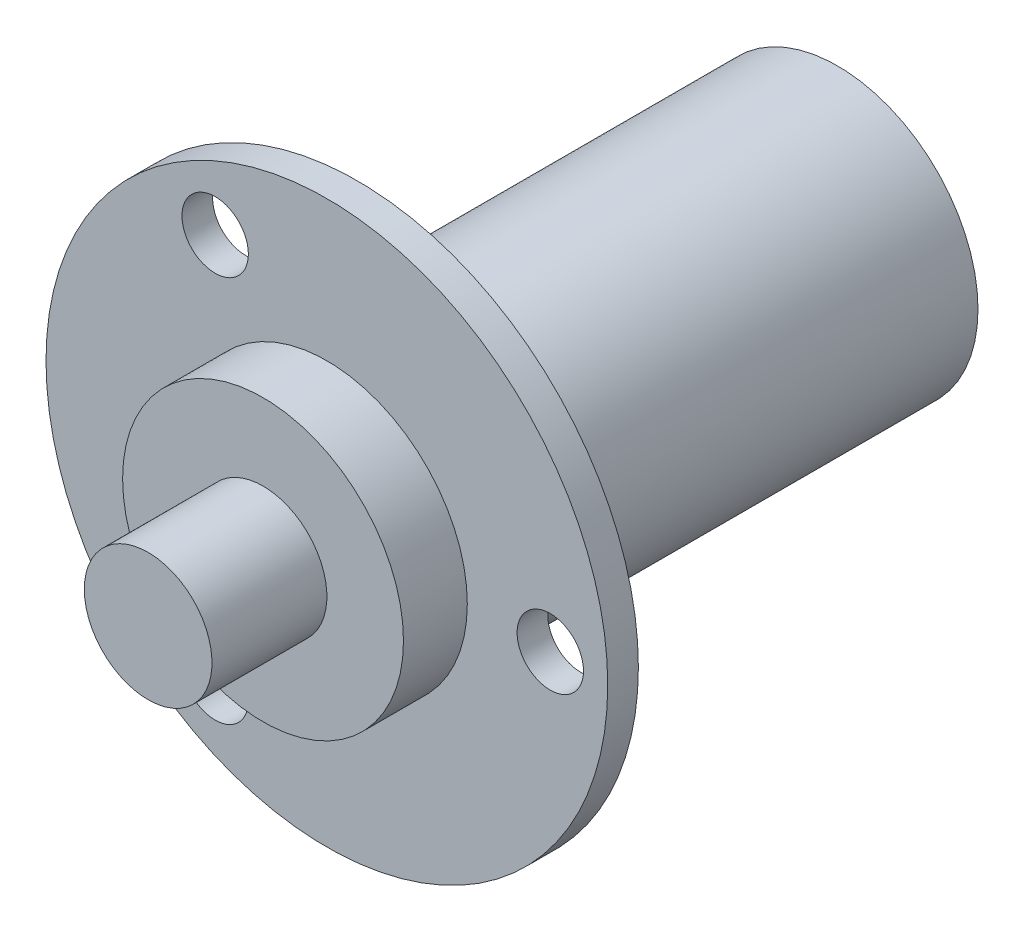
SolidWorks part; units mm, degrees
ref_plane "前视基准面" through (0, 0, 0) normal (0, 0, 1) x (1, 0, 0)
ref_plane "上视基准面" through (0, 0, 0) normal (0, 1, 0) x (1, 0, 0)
ref_plane "右视基准面" through (0, 0, 0) normal (1, 0, 0) x (0, 0, -1)
sketch "草图1" plane through (0, 0, 0) normal (0, 1, 0) x (1, 0, 0)
  line L0 (0, 0) -> (-5, 0)
  line L1 (-5, 0) -> (-5, 9)
  line L2 (-5, 9) -> (-11, 9)
  line L3 (-11, 9) -> (-11, 14)
  line L4 (-11, 14) -> (-22, 14)
  line L5 (-22, 14) -> (-22, 16.4)
  line L6 (-22, 16.4) -> (-11, 16.4)
  line L7 (-11, 16.4) -> (-11, 54)
  line L8 (-11, 54) -> (0, 54)
  line L9 (0, 54) -> (0, 0)
  dimension "D1" = 5
  dimension "D2" = 9
  dimension "D3" = 11
  dimension "D4" = 7.4
  dimension "D5" = 5
  dimension "D6" = 22
  dimension "D7" = 45
revolve "旋转1" add sketch "草图1" angle 360 about L9
sketch "草图2" plane through (0, 0, -14) normal (0, 0, 1) x (1, 0, 0)
  line L0 (-8.1529, 0) -> (29.3146, 0) construction
  circle A0 centre (17.5, 0) radius 2.6
  circle A1 centre (-8.75, -15.1554) radius 2.6
  circle A2 centre (-8.75, 15.1554) radius 2.6
  point P11 (0, 0)
  dimension "D1" = 5.2
  dimension "D2" = 17.5
  dimension "D3" = 3
extrude "切除-拉伸1" cut sketch "草图2" against normal blind 10
